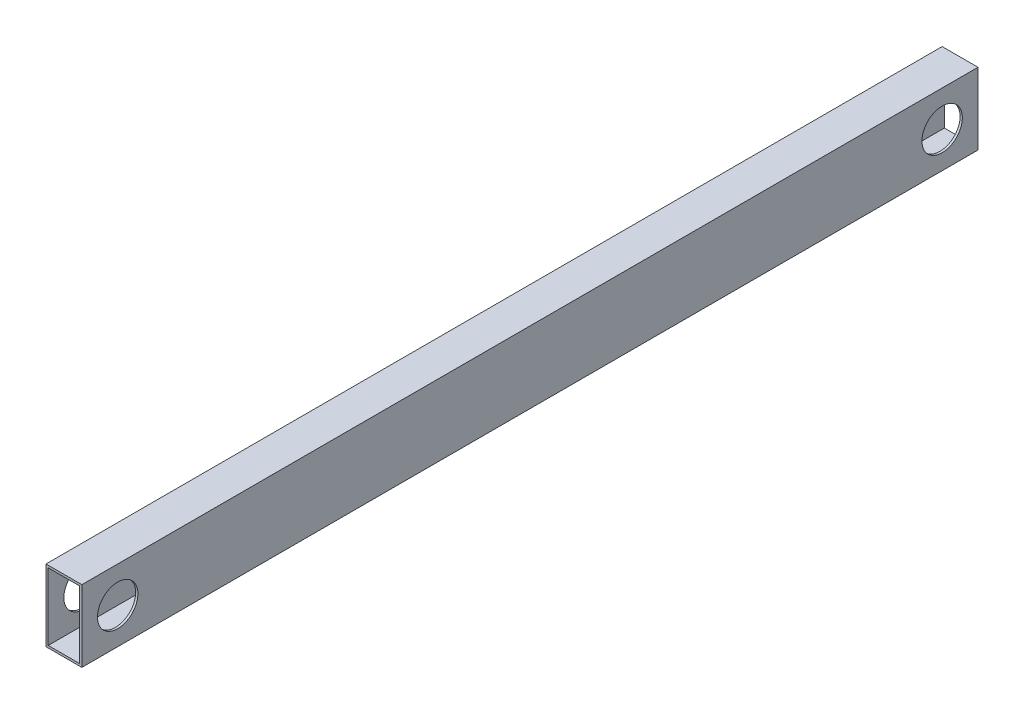
SolidWorks part; units mm, degrees
ref_plane "Front Plane" through (0, 0, 0) normal (0, 0, 1) x (1, 0, 0)
ref_plane "Top Plane" through (0, 0, 0) normal (0, 1, 0) x (1, 0, 0)
ref_plane "Right Plane" through (0, 0, 0) normal (1, 0, 0) x (0, 0, -1)
sketch "Sketch1" plane through (0, 0, 0) normal (0, 0, 1) x (1, 0, 0)
  line L0 (0, 0) -> (25.4, 50.8) construction
  line L1 (0, 0) -> (25.4, 0)
  line L2 (0, 0) -> (0, 50.8)
  line L3 (0, 50.8) -> (25.4, 50.8)
  line L4 (25.4, 0) -> (25.4, 50.8)
  line L6 (1.5875, 49.2125) -> (23.8125, 49.2125)
  line L7 (1.5875, 49.2125) -> (1.5875, 1.5875)
  line L8 (1.5875, 1.5875) -> (23.8125, 1.5875)
  line L9 (23.8125, 49.2125) -> (23.8125, 1.5875)
  line L10 (1.5875, 49.2125) -> (23.8125, 1.5875) construction
  line L11 (1.5875, 1.5875) -> (23.8125, 49.2125) construction
  point P5 (12.7, 25.4)
  point P6 (12.7, 25.4)
  dimension "D1" = 25.4
  dimension "D2" = 50.8
  dimension "D3" = 1.5875
  dimension "D4" = 1.5875
extrude "Boss-Extrude1" add sketch "Sketch1" along normal blind 635
sketch "Sketch2" plane through (25.4, 0, 0) normal (1, 0, 0) x (0, 0, -1)
  line L0 (0, 0) -> (0, 50.8) construction
  line L1 (-635, 50.8) -> (0, 50.8) construction
  line L2 (-317.5, 50.8) -> (-317.5, 104.8222) construction
  circle A0 centre (-25.4, 25.4) radius 14.3129
  circle A1 centre (-609.6, 25.4) radius 14.3129
  point P10 (-317.5, 50.8)
  point P11 (0, 0)
  dimension "D1" = 25.4
  dimension "D3" = 28.6258
  dimension "D2" = 25.4
extrude "Cut-Extrude1" cut sketch "Sketch2" against normal through all both and the other way through all
ref_plane "Plane1" through (12.7, 0, 0) normal (1, 0, 0) x (0, 0, -1)
ref_plane "Plane2" through (0, 0, 317.5) normal (0, 0, 1) x (1, 0, 0)
